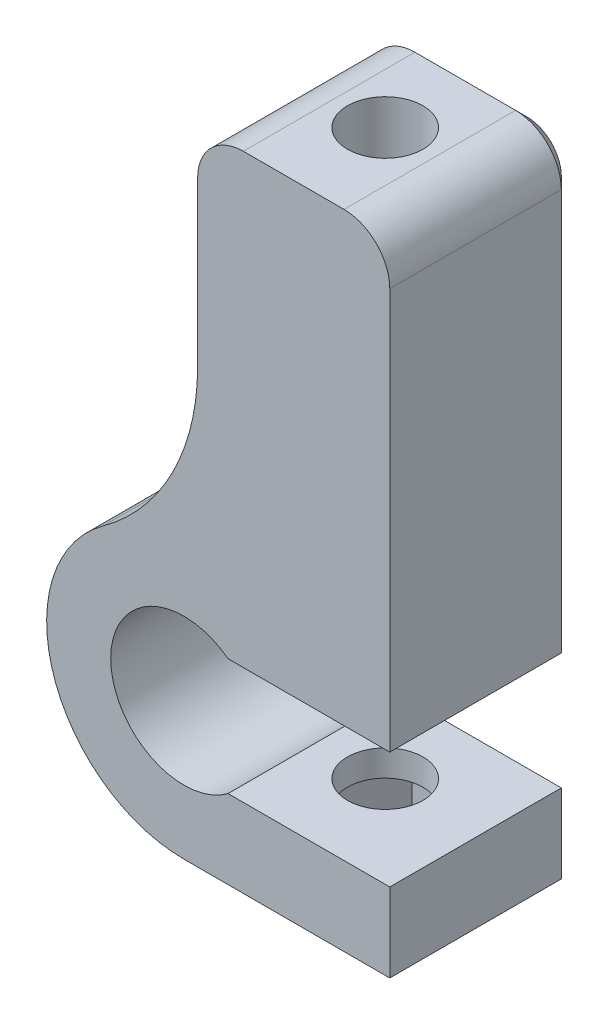
SolidWorks part; units mm, degrees
ref_plane "Front Plane" through (0, 0, 0) normal (0, 0, 1) x (1, 0, 0)
ref_plane "Top Plane" through (0, 0, 0) normal (0, 1, 0) x (1, 0, 0)
ref_plane "Right Plane" through (0, 0, 0) normal (1, 0, 0) x (0, 0, -1)
sketch "Sketch1" plane through (0, 0, 0) normal (0, 0, 1) x (1, 0, 0)
  line L0 (0, 6) -> (9, 6)
  line L1 (9, 6) -> (9, 2.5527)
  line L2 (9, 2.5527) -> (1.9297, 2.5527)
  line L3 (-11.5353, 0) -> (18.1518, 0) construction
  line L4 (9, -2.5527) -> (1.9297, -2.5527)
  line L5 (9, -6) -> (9, -2.5527)
  line L6 (0, -6) -> (9, -6)
  arc A0 (1.9297, 2.5527) -> (1.9297, -2.5527) centre (0, 0) ccw
  arc A2 (0, 6) -> (0, -6) centre (0, 0) ccw
  dimension "D1" = 3.2
  dimension "D2" = 6
  dimension "D3" = 9
  dimension "D4" = 5.1054
extrude "Boss-Extrude1" add sketch "Sketch1" along normal blind 8
sketch "Sketch2" plane through (0, -6, 0) normal (0, -1, 0) x (1, 0, 0)
  line L1 (0, 8) -> (9, 8) construction
  line L3 (0, 8) -> (0, 0) construction
  circle A0 centre (4.8, 4) radius 1.65
  dimension "D1" = 4
  dimension "D2" = 3.3
  dimension "D3" = 4.8
extrude "Cut-Extrude1" cut sketch "Sketch2" against normal through all
sketch "Sketch3" plane through (0, -6, 0) normal (0, -1, 0) x (1, 0, 0)
  line L1 (6.4, 6.7713) -> (3.2, 6.7713)
  line L2 (3.2, 6.7713) -> (1.6, 4)
  line L3 (1.6, 4) -> (3.2, 1.2287)
  line L4 (3.2, 1.2287) -> (6.4, 1.2287)
  line L5 (6.4, 1.2287) -> (8, 4)
  line L6 (8, 4) -> (6.4, 6.7713)
  circle A0 centre (4.8, 4) radius 3.2 construction
  dimension "D1" = 6.4
extrude "Cut-Extrude2" cut sketch "Sketch3" against normal blind 2.3
sketch "Sketch4" plane through (0, 0, 0) normal (0, 0, -1) x (-1, 0, 0)
  line L1 (-7.1852, 22.1) -> (24.2836, 22.1)
  line L2 (-7.1852, 22.1) -> (-11.8268, 22.1)
  line L3 (-9, 2.5527) -> (-9, 6) construction
  line L4 (-9, 2.5527) -> (-9, 6)
sketch "Sketch5" plane through (0, 6, 0) normal (0, 1, 0) x (1, 0, 0)
  line L1 (0.6, -8) -> (9, -8)
  line L2 (0.6, -8) -> (0.6, 0)
  line L3 (0.6, 0) -> (9, 0)
  line L4 (9, -8) -> (9, 0)
  line L5 (0.6, -8) -> (9, 0) construction
  line L6 (0.6, 0) -> (9, -8) construction
  circle A0 centre (4.8, -4) radius 1.65 construction
  circle A1 centre (4.8, -4) radius 1.65
extrude "Boss-Extrude2" add sketch "Sketch5" along normal up to vertex (16.1 mm away) up to point (7.1852, 22.1, 0)
fillet "Fillet1" radius 10 1 edges at (0.6, 6, 4)
fillet "Fillet2" radius 2 2 edges at (9, 22.1, 4) (0.6, 22.1, 4)
chamfer "Chamfer1" distance 0.5 angle 45 12 edges at (5.4648, 2.5527, 0) (5.4648, -2.5527, 0) (-3.2, 0, 0) (9, 11.3264, 0) (8.4142, 21.5142, 0) (4.8, 22.1, 0) (1.1858, 21.5142, 0) (0.6, 16.5238, 0) (-0.4907, 8.4061, 0) (-5.7067, -1.8531, 0) (4.5, -6, 0) (9, -4.2764, 0)
